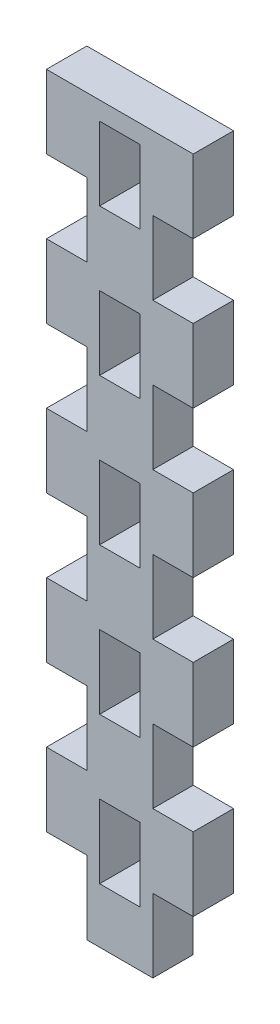
SolidWorks part; units mm, degrees
material "ﾁｰｸ材"
ref_plane "正面" through (0, 0, 0) normal (0, 0, 1) x (1, 0, 0)
ref_plane "平面" through (0, 0, 0) normal (0, 1, 0) x (1, 0, 0)
ref_plane "右側面" through (0, 0, 0) normal (1, 0, 0) x (0, 0, -1)
sketch "ｽｹｯﾁ1" plane through (0, 0, 0) normal (0, 0, 1) x (1, 0, 0)
  line L1 (10, 50) -> (-10, 50)
  line L2 (10, 50) -> (10, -50)
  line L3 (10, -50) -> (-10, -50)
  line L4 (-10, 50) -> (-10, -50)
  line L5 (10, 50) -> (-10, -50) construction
  line L6 (10, -50) -> (-10, 50) construction
  point P0 (0, 0)
  dimension "D1" = 20
  dimension "D2" = 100
extrude "ﾎﾞｽ - 押し出し1" add sketch "ｽｹｯﾁ1" along normal blind 5.5
sketch "ｽｹｯﾁ2" plane through (0, 0, 5.5) normal (0, 0, 1) x (1, 0, 0)
  line L0 (-10, 50) -> (-10, -50) construction
  line L1 (-10, 40) -> (-4.5, 40)
  line L2 (-10, 40) -> (-10, 30)
  line L3 (-10, 30) -> (-4.5, 30)
  line L4 (-4.5, 40) -> (-4.5, 30)
  line L5 (10, 50) -> (-10, 50) construction
  line L6 (-10, 20) -> (-10, 10)
  line L7 (-10, 20) -> (-4.5, 20)
  line L8 (-4.5, 20) -> (-4.5, 10)
  line L9 (-10, 10) -> (-4.5, 10)
  line L10 (-10, 0) -> (-10, -10)
  line L11 (-10, 0) -> (-4.5, 0)
  line L12 (-4.5, 0) -> (-4.5, -10)
  line L13 (-10, -10) -> (-4.5, -10)
  line L14 (-10, -20) -> (-10, -30)
  line L15 (-10, -20) -> (-4.5, -20)
  line L16 (-4.5, -20) -> (-4.5, -30)
  line L17 (-10, -30) -> (-4.5, -30)
  line L18 (0, 0) -> (0, 9.1802) construction
  line L19 (10, -20) -> (4.5, -20)
  line L20 (4.5, -20) -> (4.5, -30)
  line L21 (10, -30) -> (4.5, -30)
  line L22 (10, -20) -> (10, -30)
  line L23 (10, 0) -> (4.5, 0)
  line L24 (4.5, 0) -> (4.5, -10)
  line L25 (10, -10) -> (4.5, -10)
  line L26 (10, 0) -> (10, -10)
  line L27 (10, 20) -> (4.5, 20)
  line L28 (4.5, 20) -> (4.5, 10)
  line L29 (10, 10) -> (4.5, 10)
  line L30 (10, 20) -> (10, 10)
  line L31 (10, 30) -> (4.5, 30)
  line L32 (4.5, 40) -> (4.5, 30)
  line L33 (10, 40) -> (4.5, 40)
  line L34 (10, 40) -> (10, 30)
  line L35 (-10, -40) -> (-10, -50)
  line L36 (-10, -40) -> (-4.5, -40)
  line L37 (-4.5, -40) -> (-4.5, -50)
  line L38 (-10, -50) -> (-4.5, -50)
  line L39 (10, -40) -> (4.5, -40)
  line L40 (4.5, -40) -> (4.5, -50)
  line L41 (10, -50) -> (4.5, -50)
  line L42 (10, -40) -> (10, -50)
  dimension "D1" = 10
  dimension "D2" = 5.5
  dimension "D3" = 10
  dimension "D4" = 5
extrude "ｶｯﾄ - 押し出し1" cut sketch "ｽｹｯﾁ2" against normal through all
sketch "ｽｹｯﾁ3" plane through (0, 0, 5.5) normal (0, 0, 1) x (1, 0, 0)
  line L0 (-4.5, -50) -> (4.5, -50) construction
  line L1 (-2.75, -42.5) -> (2.75, -42.5)
  line L2 (-2.75, -42.5) -> (-2.75, -32.5)
  line L3 (-2.75, -32.5) -> (2.75, -32.5)
  line L4 (2.75, -42.5) -> (2.75, -32.5)
  line L5 (-2.75, -42.5) -> (2.75, -32.5) construction
  line L6 (-2.75, -32.5) -> (2.75, -42.5) construction
  line L7 (-2.75, -22.5) -> (-2.75, -12.5)
  line L8 (-2.75, -22.5) -> (2.75, -22.5)
  line L9 (2.75, -22.5) -> (2.75, -12.5)
  line L10 (-2.75, -12.5) -> (2.75, -12.5)
  line L11 (-2.75, -2.5) -> (-2.75, 7.5)
  line L12 (-2.75, -2.5) -> (2.75, -2.5)
  line L13 (2.75, -2.5) -> (2.75, 7.5)
  line L14 (-2.75, 7.5) -> (2.75, 7.5)
  line L15 (-2.75, 17.5) -> (-2.75, 27.5)
  line L16 (-2.75, 17.5) -> (2.75, 17.5)
  line L17 (2.75, 17.5) -> (2.75, 27.5)
  line L18 (-2.75, 27.5) -> (2.75, 27.5)
  line L19 (-2.75, 37.5) -> (-2.75, 47.5)
  line L20 (-2.75, 37.5) -> (2.75, 37.5)
  line L21 (2.75, 37.5) -> (2.75, 47.5)
  line L22 (-2.75, 47.5) -> (2.75, 47.5)
  point P0 (0, -37.5)
  dimension "D1" = 7.5
  dimension "D2" = 5.5
  dimension "D3" = 10
  dimension "D4" = 5
extrude "ｶｯﾄ - 押し出し2" cut sketch "ｽｹｯﾁ3" against normal through all
